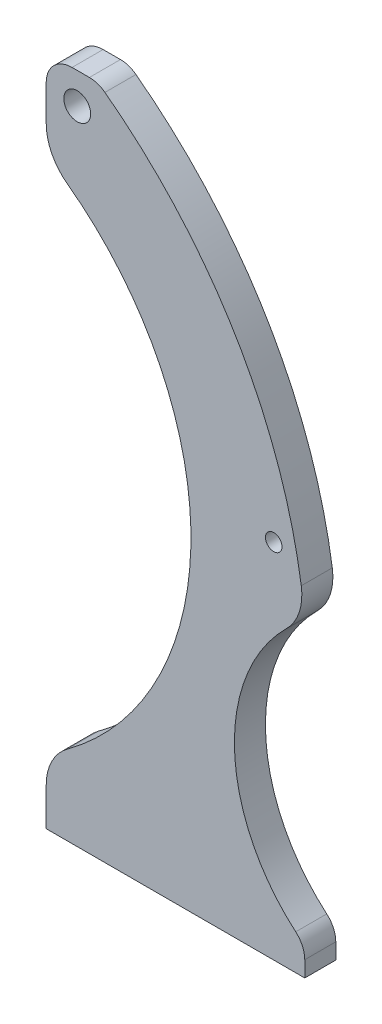
SolidWorks part; units mm, degrees
ref_plane "Plan de face" through (0, 0, 0) normal (0, 0, 1) x (1, 0, 0)
ref_plane "Plan de dessus" through (0, 0, 0) normal (0, 1, 0) x (1, 0, 0)
ref_plane "Plan de droite" through (0, 0, 0) normal (1, 0, 0) x (0, 0, -1)
sketch "Esquisse1" plane through (0, 0, 0) normal (0, 0, 1) x (1, 0, 0)
  line L1 (-27.9378, 53.975) -> (22.0622, 53.975)
  line L2 (-27.9378, 53.975) -> (-27.9378, -76.025)
  line L3 (-27.9378, -76.025) -> (22.0622, -76.025)
  line L4 (22.0622, 53.975) -> (22.0622, -76.025)
  dimension "D2" = 130
extrude "Extrusion1" add sketch "Esquisse1" along normal blind 6
ref_plane "Plan1" through (-27.9378, 53.975, 6) normal (-1, 0, 0) x (0, 0, 1)
ref_plane "Plan2" through (-27.9378, 53.975, 6) normal (-1, 0, 0) x (0, 0, 1)
sketch "Esquisse3" plane through (0, 0, 6) normal (0, 0, 1) x (1, 0, 0)
  line L0 (-7.9378, 53.975) -> (22.0622, 3.975)
  line L1 (22.0622, 53.975) -> (-27.9378, 53.975) construction
  line L2 (22.0622, -76.025) -> (22.0622, 53.975) construction
  line L3 (-27.9378, 53.975) -> (-27.9378, -76.025) construction
  line L4 (-27.9378, -76.025) -> (22.0622, -76.025) construction
  line L5 (-7.9378, 53.975) -> (22.0622, 53.975)
  line L6 (22.0622, 53.975) -> (22.0622, 3.975)
  circle A0 centre (-21.9378, 47.975) radius 2.6
  circle A1 centre (16.0622, -6.025) radius 1.6
  dimension "D3" = 5.2
  dimension "D4" = 6
  dimension "D5" = 6
  dimension "D6" = 6
  dimension "D7" = 70
  dimension "D8" = 3.2
  dimension "D1" = 20
  dimension "D2" = 80
extrude "Enlèv. mat.-Extru.1" cut sketch "Esquisse3" against normal blind 6
sketch "Esquisse4" plane through (0, 0, 6) normal (0, 0, 1) x (1, 0, 0)
  line L0 (-27.9378, 67.725) -> (-27.9378, 40.225) construction
  line L1 (-7.9378, 53.975) -> (-27.9378, 53.975) construction
  line L2 (22.0622, -76.025) -> (22.0622, 3.975) construction
  line L3 (-27.9378, 36.7856) -> (-27.9378, -63.408)
  line L4 (-17.9378, 53.975) -> (9.1226, 53.975)
  line L5 (9.1226, 53.975) -> (35.0987, 7.6288)
  line L6 (35.0987, 7.6288) -> (22.0622, -70.5647)
  arc A0 (-27.9378, -63.408) -> (-27.9378, 36.7856) centre (-58.7765, -13.3112) ccw
  arc A1 (-17.9378, 53.975) -> (22.0622, -16.2269) centre (-75.3284, -25.222) cw
  arc A2 (22.0622, -16.2269) -> (22.0622, -70.5647) centre (42.3827, -43.3958) ccw
extrude "Enlèv. mat.-Extru.2" cut sketch "Esquisse4" against normal blind 20
fillet "Congé1" radius 10 3 edges at (-27.9378, -63.408, 3) (-27.9378, 36.7856, 3) (22.0622, -16.2269, 3)
fillet "Congé2" radius 5 3 edges at (22.0622, -70.5647, 3) (-17.9378, 53.975, 3) (-27.9378, 53.975, 3)
